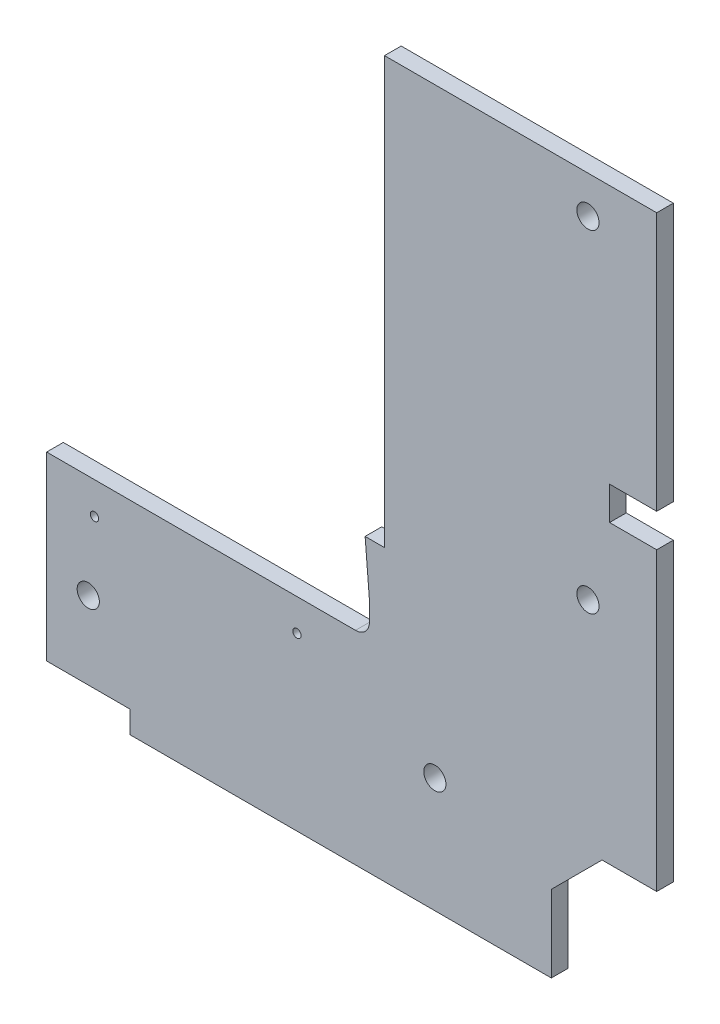
SolidWorks part; units mm, degrees
ref_plane "Front Plane" through (0, 0, 0) normal (0, 0, 1) x (1, 0, 0)
ref_plane "Top Plane" through (0, 0, 0) normal (0, 1, 0) x (1, 0, 0)
ref_plane "Right Plane" through (0, 0, 0) normal (1, 0, 0) x (0, 0, -1)
sketch "Sketch1" plane through (0, 0, 0) normal (0, 0, 1) x (1, 0, 0)
  line L0 (0, 0) -> (-220, 0)
  line L1 (-220, 0) -> (-220, 71.45)
  line L3 (-60, 259.8) -> (0, 259.8)
  line L4 (0, 259.8) -> (0, 0)
  line L5 (-140, 71.45) -> (-140, 58.45) construction
  line L6 (-210, 71.45) -> (-140, 71.45) construction
  line L7 (-210, 71.45) -> (-210, 27.79) construction
  line L8 (-210, 27.79) -> (-110, 27.79) construction
  line L9 (-110, 58.45) -> (-110, 27.79) construction
  line L10 (-140, 58.45) -> (-110, 58.45) construction
  line L11 (-220, 71.45) -> (-116.3894, 71.45)
  line L12 (-101.8943, 82.9131) -> (-60, 259.8)
  arc A5 (-116.3894, 71.45) -> (-101.8943, 82.9131) centre (-116.3894, 86.3461) ccw
  dimension "D1" = 259.8
  dimension "D2" = 220
  dimension "D3" = 71.45
  dimension "D4" = 43.66
  dimension "D5" = 100
  dimension "D6" = 27.79
  dimension "D7" = 10
  dimension "D8" = 70
  dimension "D9" = 13
  dimension "D10" = 71.45
  dimension "D11" = 14.4951
  dimension "D12" = 60
  dimension "D15" = 11.4631
extrude "Boss-Extrude2" add sketch "Sketch1" along normal blind 6
sketch "Sketch2" plane through (0, 0, 6) normal (0, 0, 1) x (1, 0, 0)
  line L0 (-220, 0) -> (0, 0) construction
  line L1 (-220, 0) -> (-190, 0)
  line L2 (-220, 0) -> (-220, 8.3)
  line L3 (-220, 8.3) -> (-190, 8.3)
  line L4 (-190, 0) -> (-190, 8.3)
  line L5 (-38, 0) -> (-38, 19)
  line L6 (-220, 71.45) -> (-220, 0) construction
  line L7 (-190, 46.3) -> (-220, 46.3) construction
  line L8 (-190, 8.3) -> (-190, 46.3) construction
  line L11 (-10.7, 46.3) -> (0, 46.3)
  line L12 (0, 0) -> (0, 259.8) construction
  line L20 (-38, 0) -> (0, 0)
  line L21 (0, 0) -> (0, 259.8) construction
  line L24 (0, 259.8) -> (-60, 259.8) construction
  line L25 (-9.8, 259.8) -> (-9.8, 0) construction
  line L26 (-190, 8.3) -> (0, 8.3) construction
  line L28 (0, 0) -> (0, 46.3)
  line L29 (-38, 19) -> (-10.7, 46.3)
  circle A0 centre (-205, 36.3) radius 4
  circle A2 centre (-24.8, 244.8) radius 4
  circle A3 centre (-24.8, 125) radius 4
  circle A5 centre (-80, 36.3) radius 4
  dimension "D3" = 8
  dimension "D6" = 15
  dimension "D12" = 8
  dimension "D14" = 8
  dimension "D1" = 8.3
  dimension "D2" = 30
  dimension "D4" = 28
  dimension "D5" = 15
  dimension "D7" = 38
  dimension "D8" = 45
  dimension "D9" = 19
  dimension "D10" = 38
  dimension "D11" = 46.3
  dimension "D13" = 140
  dimension "D15" = 28
  dimension "D17" = 24.8
  dimension "D18" = 9.8
  dimension "D21" = 125
extrude "Cut-Extrude1" cut sketch "Sketch2" against normal through all
sketch "Croquis1" plane through (0, 0, 6) normal (0, 0, 1) x (1, 0, 0)
  line L1 (-220, 71.45) -> (-116.3894, 71.45)
  line L2 (-220, 71.45) -> (-220, 73.01)
  line L3 (-220, 73.01) -> (-116.3894, 73.01)
  line L4 (-116.3894, 71.45) -> (-116.3894, 73.01)
extrude "Saliente-Extruir2" add sketch "Croquis1" against normal blind 6
sketch "Croquis3" plane through (0, 0, 6) normal (0, 0, 1) x (1, 0, 0)
  line L0 (-116.3894, 86.3461) -> (-101.8943, 82.9131) construction
  line L1 (-101.8943, 82.9131) -> (-103.4123, 83.2726)
  line L2 (-103.4123, 83.2726) -> (-60, 259.8)
  line L3 (-60, 259.8) -> (-101.8943, 82.9131)
extrude "Saliente-Extruir3" add sketch "Croquis3" against normal blind 6
sketch "Croquis4" plane through (0, 0, 6) normal (0, 0, 1) x (1, 0, 0)
  line L0 (-116.3894, 71.45) -> (-116.3894, 73.01) construction
  line L1 (-103.4123, 83.2726) -> (-101.8943, 82.9131)
  line L2 (-116.3894, 73.01) -> (-116.3894, 71.45)
  arc A0 (-101.8943, 82.9131) -> (-116.3894, 71.45) centre (-116.3894, 86.3461) cw
  arc A1 (-103.4123, 83.2726) -> (-116.3894, 73.01) centre (-116.3894, 86.3461) cw
extrude "Saliente-Extruir4" add sketch "Croquis4" against normal blind 6
sketch "Croquis5" plane through (0, 0, 6) normal (0, 0, 1) x (1, 0, 0)
  line L0 (-105, 102.74) -> (-55, 102.74)
  line L1 (-190, 8.3) -> (-220, 8.3) construction
  line L2 (-220, 73.01) -> (-220, 8.3) construction
  line L3 (-105, 102.74) -> (-103.4123, 83.2726)
  line L4 (-103.4123, 83.2726) -> (-55, 102.74)
  dimension "D1" = 94.44
  dimension "D2" = 115
  dimension "D3" = 50
extrude "Saliente-Extruir5" add sketch "Croquis5" against normal blind 6
sketch "Croquis6" plane through (0, 0, 6) normal (0, 0, 1) x (1, 0, 0)
  line L0 (-98.1575, 104.64) -> (-105.155, 104.64)
  line L1 (-60, 259.8) -> (-98.6248, 102.74) construction
  line L2 (-190, 8.3) -> (-220, 8.3) construction
  line L3 (-105, 102.74) -> (-105.155, 104.64)
  line L4 (-105, 102.74) -> (-103.4123, 83.2726) construction
  line L5 (-98.1575, 104.64) -> (-98.6248, 102.74)
  line L6 (-98.6248, 102.74) -> (-105, 102.74)
  point P6 (-101.6562, 104.64)
  dimension "D1" = 96.34
  dimension "D2" = 180
extrude "Saliente-Extruir6" add sketch "Croquis6" against normal blind 6
sketch "Croquis7" plane through (0, 0, 6) normal (0, 0, 1) x (1, 0, 0)
  line L0 (-220, 73.01) -> (-220, 73.57)
  line L1 (-220, 73.57) -> (-116.3894, 73.57)
  line L2 (-116.3894, 73.57) -> (-116.3894, 73.01)
  line L3 (-116.3894, 73.01) -> (-220, 73.01)
  dimension "D1" = 65.27
  dimension "D2" = 90
extrude "Saliente-Extruir7" add sketch "Croquis7" against normal blind 6
sketch "Croquis8" plane through (0, 0, 6) normal (0, 0, 1) x (1, 0, 0)
  line L0 (-105.155, 104.64) -> (-103.4123, 83.2726) construction
  line L1 (-116.3894, 73.57) -> (-117.9888, 71.6527)
  line L2 (-117.9888, 71.6527) -> (-105.3806, 73.0577)
  line L3 (-105.3806, 73.0577) -> (-100.6848, 83.3735)
  line L4 (-100.6848, 83.3735) -> (-103.6228, 85.8535)
  arc A0 (-116.3894, 73.57) -> (-103.6228, 85.8535) centre (-116.3894, 86.3461) ccw
extrude "Saliente-Extruir8" add sketch "Croquis8" against normal blind 6
sketch "Sketch3" plane through (0, 0, 6) normal (0, 0, 1) x (1, 0, 0)
  line L0 (-116.3894, 73.57) -> (-220, 73.57) construction
  line L1 (-220, 73.57) -> (-220, 8.3) construction
  circle A0 centre (-202.75, 62.07) radius 1.5
  circle A1 centre (-129.75, 62.07) radius 1.5
  dimension "D1" = 3
  dimension "D2" = 3
  dimension "D3" = 11.5
  dimension "D4" = 17.25
  dimension "D5" = 73
extrude "Cut-Extrude2" cut sketch "Sketch3" against normal through all
sketch "Sketch4" plane through (0, 0, 6) normal (0, 0, 1) x (1, 0, 0)
  line L0 (-103.6228, 85.8535) -> (-103.6228, 78.57)
  line L1 (-116.3894, 73.57) -> (-108.6228, 73.57)
  arc A0 (-108.6228, 73.57) -> (-103.6228, 78.57) centre (-108.6228, 78.57) ccw
  arc A1 (-103.6228, 85.8535) -> (-116.3894, 73.57) centre (-116.3894, 86.3461) cw
  dimension "D1" = 5
extrude "Cut-Extrude3" cut sketch "Sketch4" against normal through all
sketch "Croquis9" plane through (0, 0, 6) normal (0, 0, 1) x (1, 0, 0)
  line L0 (-38, 19) -> (-38, 0) construction
  line L1 (-190, 0) -> (-38, 0)
  line L2 (-190, 0) -> (-190, 0.3)
  line L3 (-190, 0.3) -> (-38, 0.3)
  line L4 (-38, 0) -> (-38, 0.3)
extrude "Cortar-Extruir1" cut sketch "Croquis9" against normal blind 10
sketch "Croquis11" plane through (0, 0, 6) normal (0, 0, 1) x (1, 0, 0)
  line L0 (-10.7, 46.3) -> (-19.7, 46.3)
  line L1 (-38, 19) -> (-38, 28)
  line L2 (-38, 28) -> (-19.7, 46.3)
  line L3 (-38, 19) -> (-10.7, 46.3)
extrude "Cortar-Extruir2" cut sketch "Croquis11" against normal blind 6
sketch "Croquis14" plane through (0, 0, 6) normal (0, 0, 1) x (1, 0, 0)
  line L0 (0, 46.3) -> (0, 259.8) construction
  line L1 (0, 153.05) -> (-17, 153.05)
  line L2 (0, 153.05) -> (0, 165.05)
  line L3 (0, 165.05) -> (-17, 165.05)
  line L4 (-17, 153.05) -> (-17, 165.05)
  line L5 (-38, 0.3) -> (-190, 0.3) construction
  dimension "D1" = 152.75
  dimension "D2" = 17
  dimension "D3" = 12
extrude "Cortar-Extruir4" cut sketch "Croquis14" against normal blind 10
sketch "Croquis15" plane through (0, 0, 6) normal (0, 0, 1) x (1, 0, 0)
  circle A0 centre (-80, 41.8) radius 4
  circle A1 centre (-205, 36.3) radius 4 construction
  dimension "D1" = 5.5
extrude "Cortar-Extruir5" cut sketch "Croquis15" against normal blind 10
sketch "Croquis16" plane through (0, 0, 6) normal (0, 0, 1) x (1, 0, 0)
  circle A0 centre (-80, 41.8) radius 4
extrude "Saliente-Extruir10" add sketch "Croquis16" against normal blind 6
sketch "Croquis17" plane through (0, 0, 6) normal (0, 0, 1) x (1, 0, 0)
  line L0 (-60, 259.8) -> (-112.3824, 259.8) construction
  line L1 (-98.1575, 104.64) -> (-98.1575, 259.8)
  line L2 (-98.1575, 259.8) -> (-60, 259.8)
  line L3 (-60, 259.8) -> (-98.1575, 104.64)
extrude "Saliente-Extruir11" add sketch "Croquis17" against normal blind 6
sketch "Croquis18" plane through (0, 0, 6) normal (0, 0, 1) x (1, 0, 0)
  line L0 (0, 165.05) -> (0, 259.8) construction
  line L1 (-98.1575, 259.8) -> (0, 259.8)
  line L2 (-98.1575, 259.8) -> (-98.1575, 258.3)
  line L3 (-98.1575, 258.3) -> (0, 258.3)
  line L4 (0, 259.8) -> (0, 258.3)
  line L5 (-190, 8.3) -> (-220, 8.3) construction
  dimension "D1" = 250
extrude "Cortar-Extruir6" cut sketch "Croquis18" against normal blind 6
